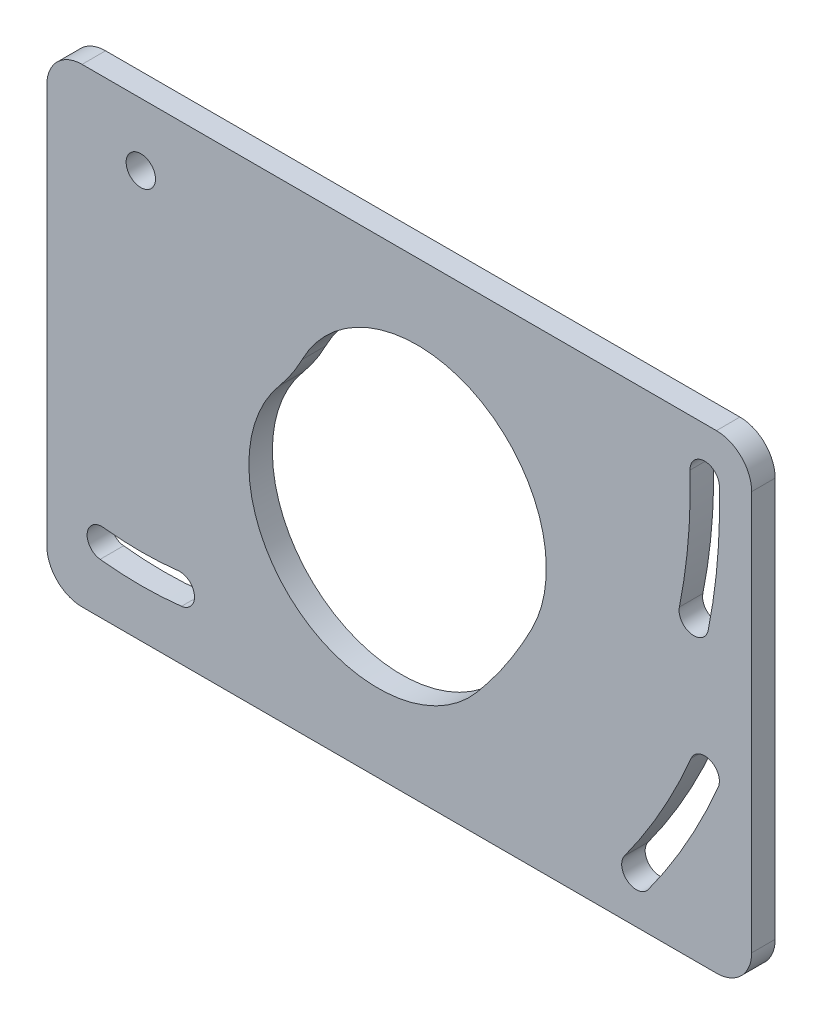
SolidWorks part; units mm, degrees
ref_plane "Płaszczyzna przednia" through (0, 0, 0) normal (0, 0, 1) x (1, 0, 0)
ref_plane "Płaszczyzna górna" through (0, 0, 0) normal (0, 1, 0) x (1, 0, 0)
ref_plane "Płaszczyzna prawa" through (0, 0, 0) normal (1, 0, 0) x (0, 0, -1)
sketch "Szkic1" plane through (0, 0, 0) normal (0, 0, 1) x (1, 0, 0)
  line L0 (-22, 14.6667) -> (-1.8017, -2.3962) construction
  line L1 (-27, -20) -> (27, -20)
  line L2 (-30, -17) -> (-30, 17)
  line L3 (-27, 20) -> (27, 20)
  line L4 (30, -17) -> (30, 17)
  line L5 (-30, -20) -> (30, 20) construction
  line L6 (-30, 20) -> (30, -20) construction
  line L7 (-18.6794, -14.4781) -> (-22, 14.6667) construction
  line L8 (-22, 14.6667) -> (-25.3206, -14.4781) construction
  line L9 (-22, 14.6667) -> (20.1826, -16) construction
  line L10 (26, 16) -> (-22, 14.6667) construction
  line L11 (-22, 14.6667) -> (25.0697, 5.1682) construction
  line L12 (-22, 14.6667) -> (26, -5.725) construction
  line L13 (-87.4435, -17.3967) -> (-91.2509, 5.1201) construction
  line L14 (-91.2509, 5.1201) -> (-92.6063, -17.6761) construction
  line L15 (-22, 14.6667) -> (1.5189, 2.5848) construction
  line L16 (-105.497, -14.5762) -> (-110.484, -14.5762) construction
  line L17 (0, 57.5) -> (-1.8017, -2.3962) construction
  line L18 (1.5189, 2.5848) -> (0, 57.5) construction
  arc A0 (27, 20) -> (30, 17) centre (27, 17) cw
  arc A1 (27, -20) -> (30, -17) centre (27, -17) ccw
  arc A2 (-27, -20) -> (-30, -17) centre (-27, -17) cw
  arc A3 (-30, 17) -> (-27, 20) centre (-27, 17) cw
  circle A4 centre (-1.8017, -2.3962) radius 11 construction
  circle A5 centre (-22, 14.6667) radius 1.25
  circle A6 centre (25.0697, 5.1682) radius 1.25 construction
  circle A7 centre (-25.3206, -14.4781) radius 1.25 construction
  circle A8 centre (20.1826, -16) radius 1.25 construction
  circle A9 centre (26, -5.725) radius 1.25 construction
  circle A10 centre (-18.6794, -14.4781) radius 1.25 construction
  circle A11 centre (1.5189, 2.5848) radius 11 construction
  circle A12 centre (26, 16) radius 1.25 construction
  circle A13 centre (-22, 14.6667) radius 26.4407 construction
  circle A14 centre (-22, 14.6667) radius 48.0185 construction
  circle A15 centre (-22, 14.6667) radius 52.1519 construction
  circle A16 centre (-22, 14.6667) radius 29.3333 construction
  arc A17 (24.7495, 16) -> (24.7426, 13.1103) centre (-22, 14.6667) cw
  arc A18 (-18.6794, -14.4781) -> (-25.3206, -14.4781) centre (-22, 14.6667) cw construction
  arc A19 (-25.4621, -15.7201) -> (-18.5379, -15.7201) centre (-22, 14.6667) ccw
  arc A20 (-25.1791, -13.2361) -> (-18.8209, -13.2361) centre (-22, 14.6667) ccw
  arc A21 (-25.1791, -13.2361) -> (-25.4621, -15.7201) centre (-25.3206, -14.4781) ccw
  arc A22 (-18.5379, -15.7201) -> (-18.8209, -13.2361) centre (-18.6794, -14.4781) ccw
  arc A23 (26, 16) -> (25.0697, 5.1682) centre (-22, 14.6667) cw construction
  arc A24 (26.295, 4.9209) -> (27.2495, 16.0347) centre (-22, 14.6667) ccw
  arc A25 (23.8444, 5.4154) -> (24.7505, 15.9653) centre (-22, 14.6667) ccw
  arc A26 (23.8444, 5.4154) -> (26.295, 4.9209) centre (25.0697, 5.1682) ccw
  arc A27 (27.2495, 16.0347) -> (24.7505, 15.9653) centre (26, 16) ccw
  arc A28 (26, -5.725) -> (20.1826, -16) centre (-22, 14.6667) cw construction
  arc A29 (21.1937, -16.735) -> (27.1505, -6.2137) centre (-22, 14.6667) ccw
  arc A30 (19.1716, -15.265) -> (24.8495, -5.2362) centre (-22, 14.6667) ccw
  arc A31 (19.1716, -15.265) -> (21.1937, -16.735) centre (20.1826, -16) ccw
  arc A32 (27.1505, -6.2137) -> (24.8495, -5.2362) centre (26, -5.725) ccw
  arc A33 (1.5189, 2.5848) -> (-1.8017, -2.3962) centre (-22, 14.6667) cw construction
  arc A34 (6.6013, -9.4948) -> (11.3033, -2.4416) centre (-22, 14.6667) ccw
  arc A35 (-10.2047, 4.7024) -> (-8.2656, 7.6111) centre (-22, 14.6667) ccw
  arc A36 (-10.2047, 4.7024) -> (6.6013, -9.4948) centre (-1.8017, -2.3962) ccw
  arc A37 (11.3033, -2.4416) -> (-8.2656, 7.6111) centre (1.5189, 2.5848) ccw
  point P0 (1.5189, 2.5848)
  point P40 (-22, -14.6667)
  point P48 (25.8424, 10.5577)
  point P55 (23.383, -11.0277)
  point P62 (0, 0)
  point P73 (0, 57.5)
  point P75 (-110.484, -14.5762)
  point P78 (-110.484, -11.124)
  point P79 (-107.0298, -14.5762)
  point P80 (18.3965, 12.2703)
  point P81 (25.0378, 11.5446)
  point P82 (0, 0)
  point P83 (22, -8.2689)
  point P87 (22, -10.229)
  point P88 (24.4581, -4.4096)
  point P89 (18.8945, -15.0889)
  point P90 (23.1098, -53.684)
  point P91 (23.1098, -10.9763)
  point P92 (22, -11.6538)
  point P93 (22.6296, -9.4948)
  dimension "D3" = 3
  dimension "D4" = 2.5
  dimension "D9" = 22
  dimension "D14" = 11
  dimension "D15" = 1.25
  dimension "D16" = 1.25
  dimension "D17" = 1.25
  dimension "D1" = 60
  dimension "D2" = 40
  dimension "D5" = 8
  dimension "D10" = 13
  dimension "D12" = 13
  dimension "D18" = 13
  dimension "D6" = 8
  dimension "D13" = 13
  dimension "D11" = 13
  dimension "D19" = 57.5
  dimension "D20" = 59.9233
  dimension "D21" = 54.9363
  dimension "D22" = 4.987
  dimension "D7" = 4
  dimension "D8" = 4
  dimension "D23" = 4
  dimension "D24" = 4
extrude "Dodanie-wyciągnięcie1" add sketch "Szkic1" along normal blind 2 contours A3 L2 A2 L1 A1 L4 A0 L3 A37 A34 A36 A35 A32 A29 A31 A30 A27 A24 A26 A17 A22 A19 A21 A20 A5
equation "\"D12@Szkic1\"=\"D18@Szkic1\""
equation "\"D10@Szkic1\"=\"D18@Szkic1\""
equation "\"D13@Szkic1\"=\"D18@Szkic1\""
equation "\"D11@Szkic1\"=\"D18@Szkic1\""
equation "\"D22@Szkic1\"=\"D20@Szkic1\"-\"D21@Szkic1\""
